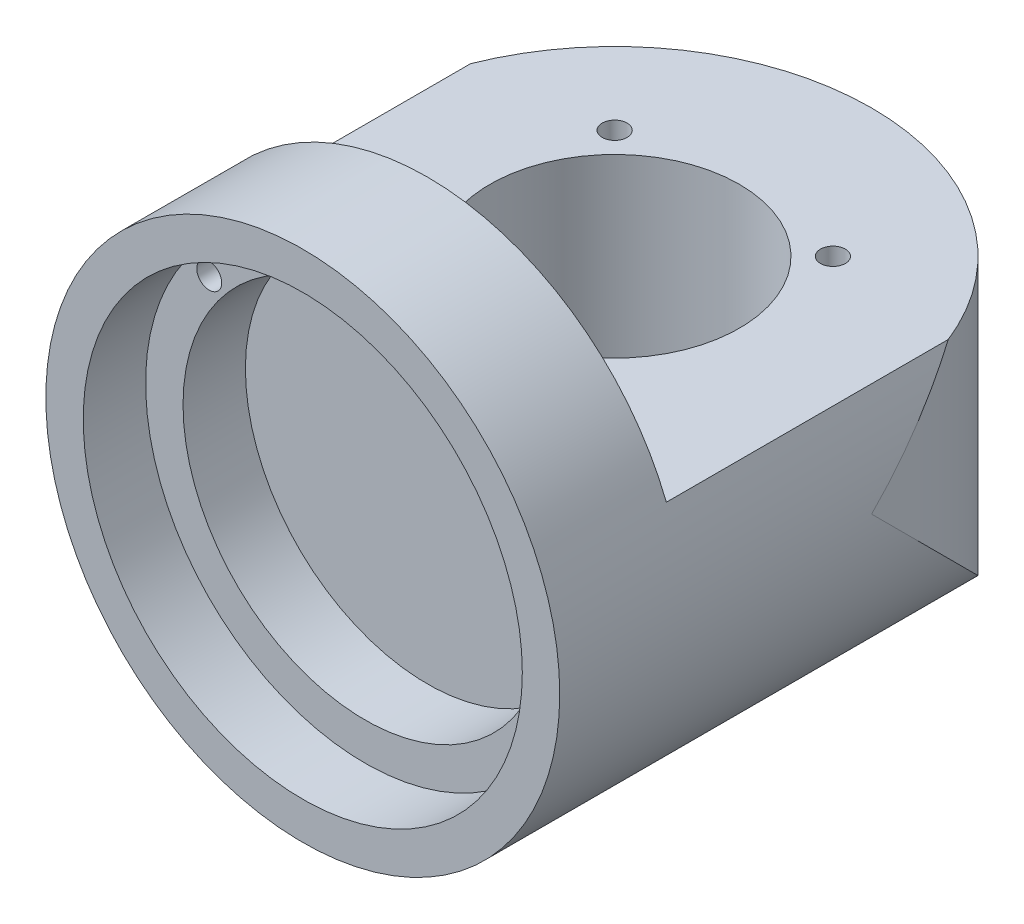
SolidWorks part; units mm, degrees
ref_plane "前视基准面" through (0, 0, 0) normal (0, 0, 1) x (1, 0, 0)
ref_plane "上视基准面" through (0, 0, 0) normal (0, 1, 0) x (1, 0, 0)
ref_plane "右视基准面" through (0, 0, 0) normal (1, 0, 0) x (0, 0, -1)
sketch "草图1" plane through (0, 0, 0) normal (0, 0, 1) x (1, 0, 0)
  circle A0 centre (0, 0) radius 41.2
extrude "凸台-拉伸1" add sketch "草图1" along normal blind 20
sketch "草图2" plane through (0, 0, 0) normal (0, 1, 0) x (1, 0, 0)
  line L0 (-41.2, 0) -> (41.2, 0)
  line L1 (-41.2, 0) -> (-41.2, 30)
  line L2 (41.2, 0) -> (41.2, 30)
  line L3 (-41.2, 30) -> (41.2, 30)
  line L4 (41.2, 0) -> (-41.2, 0) construction
  arc A0 (41.2, 30) -> (-41.2, 30) centre (0, 30) ccw
extrude "凸台-拉伸3" add sketch "草图2" along normal blind 15.2 and the other way blind 32.2 contours L3 L1 L0 L2 | L3 A0
sketch "草图3" plane through (0, 0, 0) normal (0, 0, -1) x (-1, 0, 0)
  circle A0 centre (0, 0) radius 41.2
extrude "切除-拉伸1" cut sketch "草图3" along normal blind 70.2 flip side to cut
sketch "草图4" plane through (0, 15.2, 0) normal (0, 1, 0) x (1, 0, 0)
  circle A0 centre (0, 30) radius 20
extrude "切除-拉伸2" cut sketch "草图4" against normal blind 43.8
sketch "草图5" plane through (0, -28.6, 0) normal (0, 1, 0) x (1, 0, 0)
  circle A0 centre (0, 30) radius 15.7
extrude "切除-拉伸3" cut sketch "草图5" against normal blind 3.6
sketch "草图6" plane through (0, -32.2, 0) normal (0, -1, 0) x (-1, 0, 0)
  line L0 (0, 0) -> (0, 30)
sketch "草图9" plane through (0, 0, 20) normal (0, 0, 1) x (1, 0, 0)
  circle A0 centre (0, 0) radius 35.2
extrude "切除-拉伸6" cut sketch "草图9" against normal blind 10
sketch "草图10" plane through (0, 0, 10) normal (0, 0, 1) x (1, 0, 0)
  circle A0 centre (0, 0) radius 29.2
extrude "切除-拉伸7" cut sketch "草图10" against normal blind 10
sketch "草图12" plane through (0, 0, 0) normal (0, 0, 1) x (1, 0, 0)
  circle A0 centre (-25, 20) radius 2
  circle A1 centre (-17, 28) radius 2
  circle A3 centre (25, 20) radius 2
  circle A4 centre (17, 28) radius 2
extrude "切除-拉伸8" cut sketch "草图12" along normal blind 10 contours A0 | A3 | A4 | A1
sketch "草图13" plane through (0, -32.2, 0) normal (0, -1, 0) x (1, 0, 0)
  circle A1 centre (0, -48) radius 2
  circle A2 centre (-12.7279, -42.7279) radius 2
  circle A4 centre (-18, -30) radius 2
  circle A5 centre (-12.7279, -17.2721) radius 2
  circle A6 centre (0, -12) radius 2
  circle A7 centre (12.7279, -17.2721) radius 2
  circle A8 centre (18, -30) radius 2
  circle A9 centre (12.7279, -42.7279) radius 2
  point P0 (0, -30)
extrude "切除-拉伸9" cut sketch "草图13" against normal blind 2.1
sketch "草图15" plane through (0, -30.1, 0) normal (0, -1, 0) x (-1, 0, 0)
  circle A1 centre (0, 48) radius 0.8
  circle A2 centre (12.7279, 42.7279) radius 0.8
  circle A3 centre (18, 30) radius 0.8
  circle A4 centre (12.7279, 17.2721) radius 0.8
  circle A5 centre (0, 12) radius 0.8
  circle A6 centre (-12.7279, 17.2721) radius 0.8
  circle A7 centre (-18, 30) radius 0.8
  circle A8 centre (-12.7279, 42.7279) radius 0.8
  point P0 (0, 30)
extrude "切除-拉伸10" cut sketch "草图15" against normal blind 1.5
sketch "草图16" plane through (0, 15.2, 0) normal (0, 1, 0) x (1, 0, 0)
  circle A1 centre (-17.5, 47.5) radius 2
  circle A2 centre (17.5, 47.5) radius 2
extrude "切除-拉伸13" cut sketch "草图16" against normal blind 40 contours A2 | A1
sketch "草图17" plane through (0, 0, 20) normal (0, 0, 1) x (1, 0, 0)
  line L0 (0, 41.2) -> (0, -41.2)
  circle A1 centre (0, 0) radius 41.2 construction
